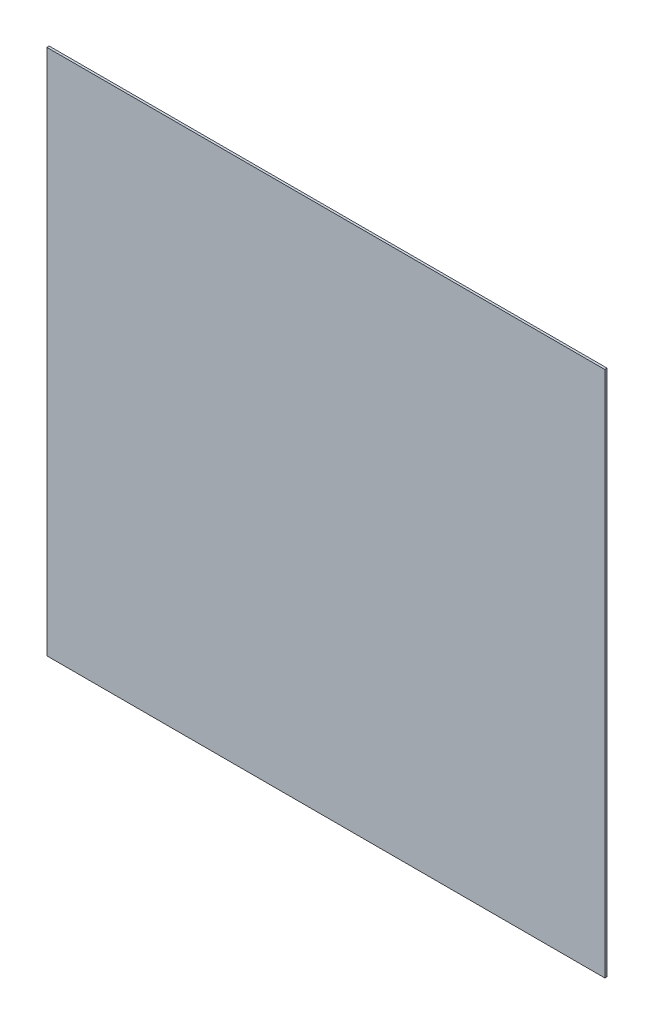
SolidWorks part; units mm, degrees
ref_plane "Front Plane" through (0, 0, 0) normal (0, 0, 1) x (1, 0, 0)
ref_plane "Top Plane" through (0, 0, 0) normal (0, 1, 0) x (1, 0, 0)
ref_plane "Right Plane" through (0, 0, 0) normal (1, 0, 0) x (0, 0, -1)
sketch "Sketch1" plane through (0, 0, 0) normal (0, 0, 1) x (1, 0, 0)
  line L1 (0, 0) -> (180, 0)
  line L2 (0, 0) -> (0, 170)
  line L3 (0, 170) -> (180, 170)
  line L4 (180, 0) -> (180, 170)
  dimension "D1" = 180
  dimension "D2" = 170
extrude "Boss-Extrude1" add sketch "Sketch1" along normal blind 0.75
